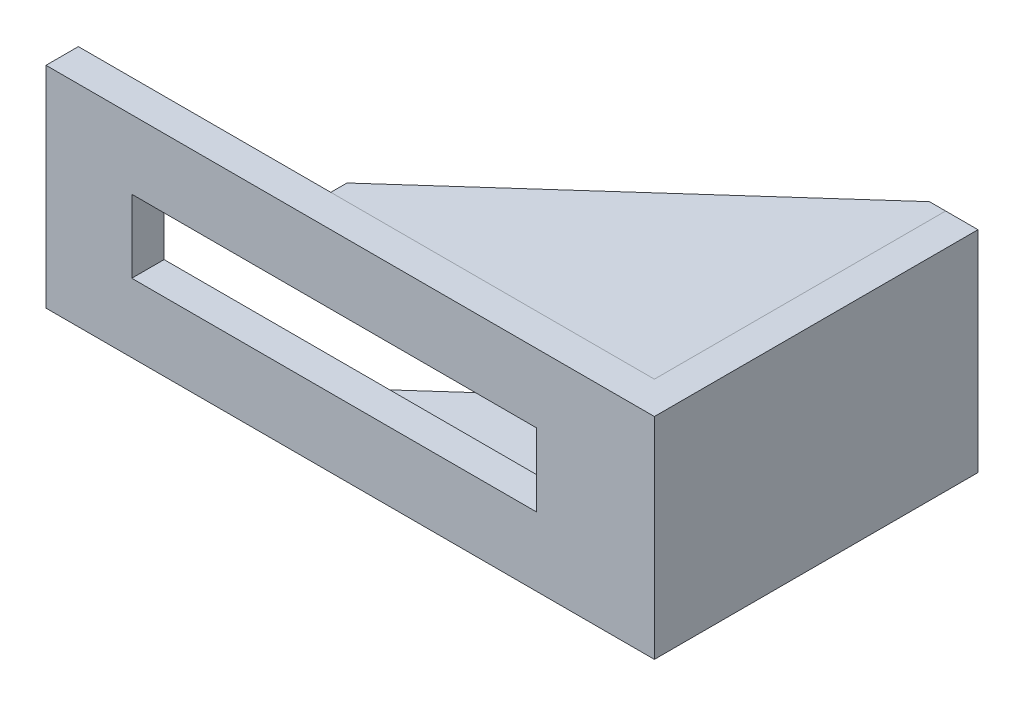
SolidWorks part; units mm, degrees
ref_plane "前视基准面" through (0, 0, 0) normal (0, 0, 1) x (1, 0, 0)
ref_plane "上视基准面" through (0, 0, 0) normal (0, 1, 0) x (1, 0, 0)
ref_plane "右视基准面" through (0, 0, 0) normal (1, 0, 0) x (0, 0, -1)
sketch "草图1" plane through (0, 0, 0) normal (0, 0, 1) x (1, 0, 0)
  line L1 (-178, 65) -> (178, 65)
  line L2 (-178, 65) -> (-178, -65)
  line L3 (-178, -65) -> (178, -65)
  line L4 (178, 65) -> (178, -65)
  line L5 (-178, 65) -> (178, -65) construction
  line L6 (-178, -65) -> (178, 65) construction
  point P0 (0, 0)
  dimension "D1" = 130
  dimension "D2" = 356
extrude "凸台-拉伸1" add sketch "草图1" along normal blind 20
sketch "草图2" plane through (178, 0, 0) normal (1, 0, 0) x (0, 0, -1)
  line L0 (-20, 65) -> (0, 65) construction
  line L1 (-20, -65) -> (180, -65)
  line L2 (-20, -65) -> (-20, 65)
  line L3 (-20, 65) -> (180, 65)
  line L4 (180, -65) -> (180, 65)
  dimension "D1" = 200
extrude "凸台-拉伸2" add sketch "草图2" along normal blind 20
sketch "草图3" plane through (0, -65, 0) normal (0, -1, 0) x (1, 0, 0)
  line L0 (178, -180) -> (168, -180)
  line L1 (168, -180) -> (-22, -10)
  line L2 (-22, -10) -> (-22, 0)
  line L3 (-178, 0) -> (178, 0) construction
  line L4 (-22, 0) -> (178, 0)
  line L5 (178, 0) -> (178, -180)
  dimension "D1" = 10
  dimension "D2" = 10
  dimension "D3" = 200
extrude "凸台-拉伸3" add sketch "草图3" against normal blind 20 separate body
mirror "镜向2" about plane through (0, 0, 0) normal (0, 1, 0) of bodies 110
sketch "草图4" plane through (0, 0, 20) normal (0, 0, 1) x (1, 0, 0)
  line L1 (-125, 22.5) -> (125, 22.5)
  line L2 (-125, 22.5) -> (-125, -22.5)
  line L3 (-125, -22.5) -> (125, -22.5)
  line L4 (125, 22.5) -> (125, -22.5)
  line L5 (-125, 22.5) -> (125, -22.5) construction
  line L6 (-125, -22.5) -> (125, 22.5) construction
  point P0 (0, 0)
  dimension "D1" = 45
  dimension "D2" = 250
extrude "切除-拉伸1" cut sketch "草图4" against normal through all
equation "\"零件重量\"= \"SW-质量\""
